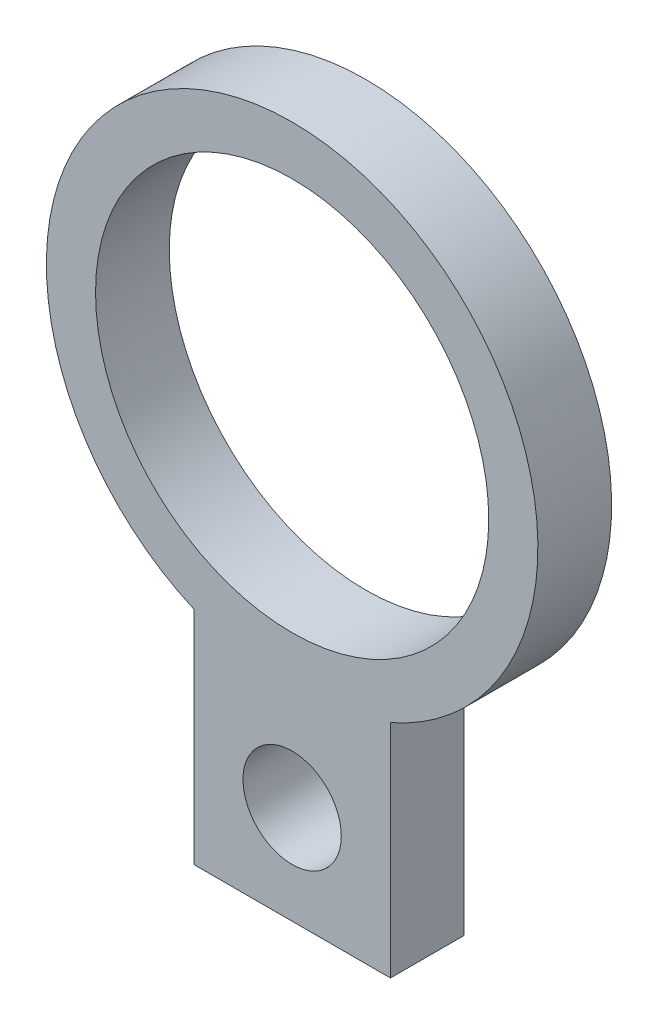
SolidWorks part; units mm, degrees
ref_plane "前视基准面" through (0, 0, 0) normal (0, 0, 1) x (1, 0, 0)
ref_plane "上视基准面" through (0, 0, 0) normal (0, 1, 0) x (1, 0, 0)
ref_plane "右视基准面" through (0, 0, 0) normal (1, 0, 0) x (0, 0, -1)
sketch "草图1" plane through (0, 0, 0) normal (0, 0, 1) x (1, 0, 0)
  line L0 (-2, -9.0826) -> (2, -9.0826)
  line L2 (2, -9.0826) -> (2, -4.5826)
  line L4 (-2, -4.5826) -> (-2, -9.0826)
  line L5 (-2, -6.0826) -> (2, -6.0826) construction
  line L6 (-2, -4.5826) -> (2, -4.5826) construction
  arc A0 (2, -4.5826) -> (-2, -4.5826) centre (0, 0) ccw
  circle A1 centre (0, -7.0826) radius 1
  circle A2 centre (0, 0) radius 4
  point P6 (0, -9.0826)
  dimension "D1" = 5
  dimension "D4" = 2
  dimension "D6" = 8
  dimension "D2" = 4
  dimension "D3" = 4.5
  dimension "D5" = 1.5
extrude "凸台-拉伸1" add sketch "草图1" along normal blind 1.5
